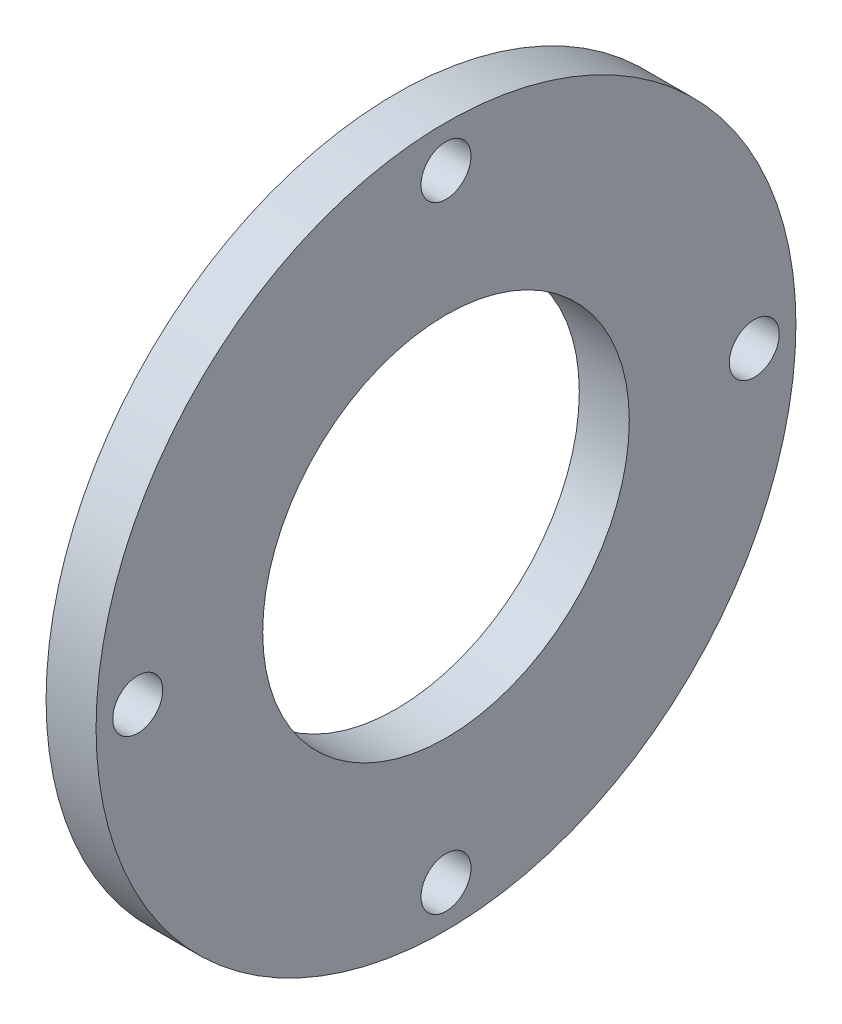
SolidWorks part; units mm, degrees
ref_plane "Front Plane" through (0, 0, 0) normal (0, 0, 1) x (1, 0, 0)
ref_plane "Top Plane" through (0, 0, 0) normal (0, 1, 0) x (1, 0, 0)
ref_plane "Right Plane" through (0, 0, 0) normal (1, 0, 0) x (0, 0, -1)
sketch "Sketch1" plane through (0, 0, 0) normal (1, 0, 0) x (0, 0, -1)
  circle A0 centre (0, 0) radius 21
  circle A1 centre (0, 0) radius 11
  circle A2 centre (0, 0) radius 18.5 construction
  circle A3 centre (0, 18.5) radius 1.5
  circle A4 centre (18.5, 0) radius 1.5
  circle A5 centre (0, -18.5) radius 1.5
  circle A6 centre (-18.5, 0) radius 1.5
  point P15 (0, 0)
  dimension "D1" = 22
  dimension "D2" = 42
  dimension "D3" = 37
  dimension "D4" = 3
  dimension "D5" = 4
extrude "Boss-Extrude1" add sketch "Sketch1" along normal blind 3
sketch "Sketch2" [suppressed] plane through (0, 0, 0) normal (-1, 0, 0) x (0, 0, 1)
  circle A0 centre (0, 0) radius 16
  circle A1 centre (0, 0) radius 11 construction
  circle A2 centre (0, 0) radius 11
  dimension "D1" = 32
extrude "Boss-Extrude2" [suppressed] add sketch "Sketch2" along normal blind 2.95
